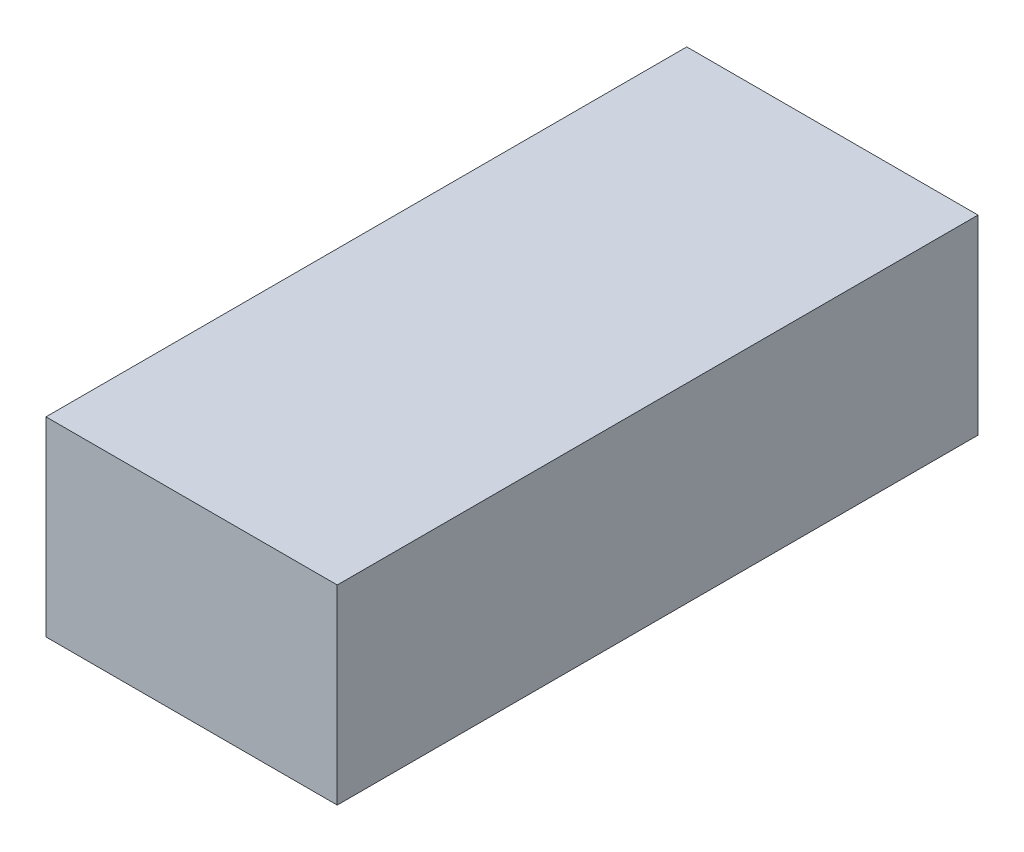
SolidWorks part; units mm, degrees
ref_plane "Front Plane" through (0, 0, 0) normal (0, 0, 1) x (1, 0, 0)
ref_plane "Top Plane" through (0, 0, 0) normal (0, 1, 0) x (1, 0, 0)
ref_plane "Right Plane" through (0, 0, 0) normal (1, 0, 0) x (0, 0, -1)
sketch "Sketch1" plane through (0, 0, 0) normal (1, 0, 0) x (0, 0, -1)
  line L1 (-121, -36) -> (121, -36)
  line L2 (-121, -36) -> (-121, 36)
  line L3 (-121, 36) -> (121, 36)
  line L4 (121, -36) -> (121, 36)
  line L5 (-121, -36) -> (121, 36) construction
  line L6 (-121, 36) -> (121, -36) construction
  point P0 (0, 0)
  dimension "D1" = 242
  dimension "D2" = 72
extrude "Boss-Extrude1" add sketch "Sketch1" along normal blind 110
shell "Shell1" thickness 4
